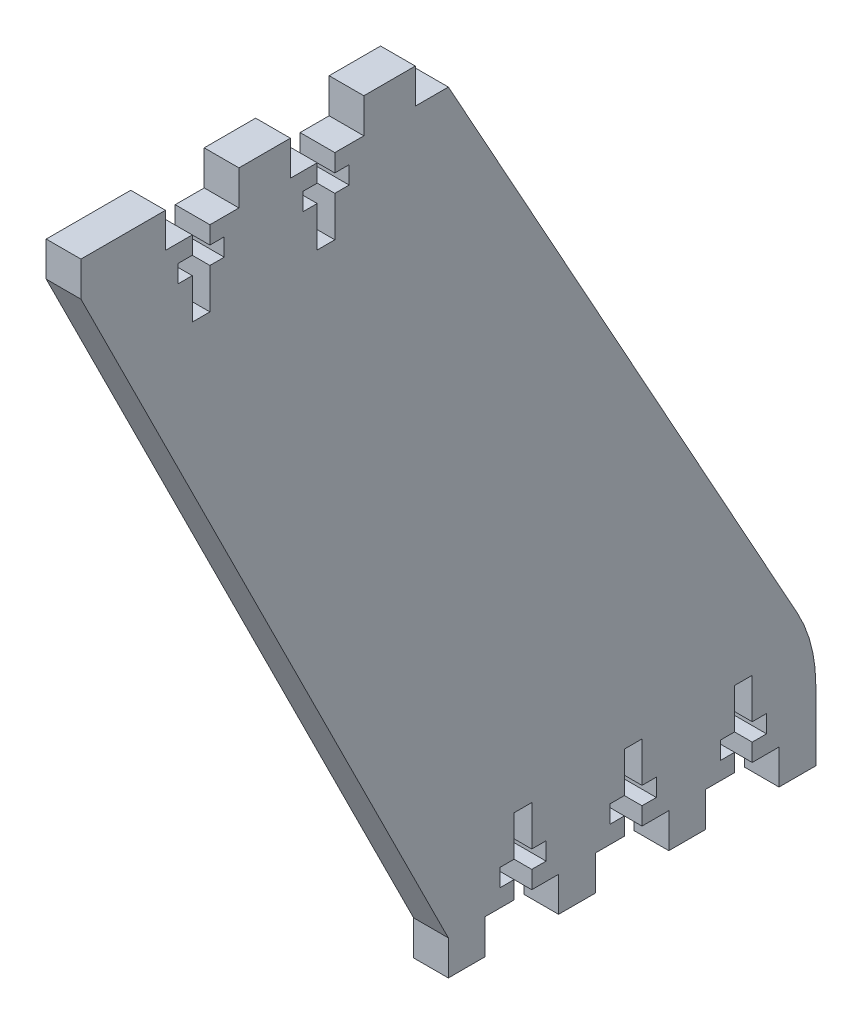
SolidWorks part; units mm, degrees
ref_plane "Front Plane" through (0, 0, 0) normal (0, 0, 1) x (1, 0, 0)
ref_plane "Top Plane" through (0, 0, 0) normal (0, 1, 0) x (1, 0, 0)
ref_plane "Right Plane" through (0, 0, 0) normal (1, 0, 0) x (0, 0, -1)
sketch "Sketch1" plane through (0, 0, 0) normal (1, 0, 0) x (0, 0, -1)
  line L0 (-74.3254, 0) -> (74.3254, 0) construction
  line L1 (-31.75, 0) -> (-95.25, 127.35)
  line L4 (-31.75, 0) -> (0, 17.1799) construction
  line L5 (-95.25, 127.35) -> (-95.25, 133.35)
  line L6 (-95.25, 133.35) -> (-80.645, 133.35)
  line L7 (-80.645, 133.35) -> (-80.645, 127.35)
  line L8 (-80.645, 127.35) -> (-67.945, 127.35)
  line L9 (-67.945, 127.35) -> (-67.945, 133.35)
  line L10 (-67.945, 133.35) -> (-59.055, 133.35)
  line L11 (-59.055, 133.35) -> (-59.055, 127.35)
  line L12 (-59.055, 127.35) -> (-46.355, 127.35)
  line L13 (-46.355, 127.35) -> (-46.355, 133.35)
  line L14 (-46.355, 133.35) -> (-37.465, 133.35)
  line L15 (-37.465, 133.35) -> (-37.465, 127.35)
  line L16 (-37.465, 127.35) -> (-31.75, 127.35)
  line L17 (-31.75, 0) -> (-31.75, -6)
  line L18 (-31.75, -6) -> (-25.4, -6)
  line L19 (-25.4, -6) -> (-25.4, 0)
  line L20 (-25.4, 0) -> (-12.7, 0)
  line L21 (-12.7, 0) -> (-12.7, -6)
  line L22 (-12.7, -6) -> (-6.35, -6)
  line L23 (-6.35, -6) -> (-6.35, 0)
  line L24 (-6.35, 0) -> (6.35, 0)
  line L25 (6.35, 0) -> (6.35, -6)
  line L26 (6.35, -6) -> (12.7, -6)
  line L27 (12.7, -6) -> (12.7, 0)
  line L28 (12.7, 0) -> (25.4, 0)
  line L29 (25.4, 0) -> (25.4, -6)
  line L30 (25.4, -6) -> (31.75, -6)
  line L31 (31.75, -6) -> (31.75, 0)
  line L32 (0, 17.1799) -> (31.75, 0) construction
  line L33 (0, 0) -> (0, 17.1799) construction
  line L34 (-63.5, 133.35) -> (-63.5, 108.2099) construction
  line L35 (31.75, 0) -> (31.75, 6.1358)
  line L36 (28.5696, 18.4423) -> (-31.75, 127.35)
  arc A0 (31.75, 6.1358) -> (28.5696, 18.4423) centre (6.35, 6.1358) ccw
  point P37 (-74.295, 127.35)
  point P38 (-52.705, 127.35)
  point P39 (-19.05, 0)
  point P40 (19.05, 0)
  point P44 (31.75, 12.7)
  line B0 (-18.8595, 13.05) -> (-18.8595, -5.9362) construction
  line B1 (-20.3835, 0) -> (-20.3835, 3.048)
  line B2 (-20.3835, 3.048) -> (-22.86, 3.048)
  line B3 (-22.86, 3.048) -> (-22.86, 6.096)
  line B4 (-22.86, 6.096) -> (-20.3835, 6.096)
  line B5 (-20.3835, 6.096) -> (-20.3835, 13.05)
  line B6 (-20.3835, 13.05) -> (-17.3355, 13.05)
  line B7 (-17.3355, 6.096) -> (-17.3355, 13.05)
  line B8 (-14.859, 6.096) -> (-17.3355, 6.096)
  line B9 (-14.859, 3.048) -> (-14.859, 6.096)
  line B10 (-17.3355, 3.048) -> (-14.859, 3.048)
  line B11 (-17.3355, 0) -> (-17.3355, 3.048)
  line B12 (0.1905, 13.05) -> (0.1905, -5.9362) construction
  line B13 (-1.3335, 0) -> (-1.3335, 3.048)
  line B14 (-1.3335, 3.048) -> (-3.81, 3.048)
  line B15 (-3.81, 3.048) -> (-3.81, 6.096)
  line B16 (-3.81, 6.096) -> (-1.3335, 6.096)
  line B17 (-1.3335, 6.096) -> (-1.3335, 13.05)
  line B18 (-1.3335, 13.05) -> (1.7145, 13.05)
  line B19 (1.7145, 6.096) -> (1.7145, 13.05)
  line B20 (4.191, 6.096) -> (1.7145, 6.096)
  line B21 (4.191, 3.048) -> (4.191, 6.096)
  line B22 (1.7145, 3.048) -> (4.191, 3.048)
  line B23 (1.7145, 0) -> (1.7145, 3.048)
  line B24 (19.2405, 13.05) -> (19.2405, -5.9362) construction
  line B25 (17.7165, 0) -> (17.7165, 3.048)
  line B26 (17.7165, 3.048) -> (15.24, 3.048)
  line B27 (15.24, 3.048) -> (15.24, 6.096)
  line B28 (15.24, 6.096) -> (17.7165, 6.096)
  line B29 (17.7165, 6.096) -> (17.7165, 13.05)
  line B30 (17.7165, 13.05) -> (20.7645, 13.05)
  line B31 (20.7645, 6.096) -> (20.7645, 13.05)
  line B32 (23.241, 6.096) -> (20.7645, 6.096)
  line B33 (23.241, 3.048) -> (23.241, 6.096)
  line B34 (20.7645, 3.048) -> (23.241, 3.048)
  line B35 (20.7645, 0) -> (20.7645, 3.048)
  line B36 (-74.4855, 114.3) -> (-74.4855, 133.2862) construction
  line B37 (-72.9615, 127.35) -> (-72.9615, 124.302)
  line B38 (-72.9615, 124.302) -> (-70.485, 124.302)
  line B39 (-70.485, 124.302) -> (-70.485, 121.254)
  line B40 (-70.485, 121.254) -> (-72.9615, 121.254)
  line B41 (-72.9615, 121.254) -> (-72.9615, 114.3)
  line B42 (-72.9615, 114.3) -> (-76.0095, 114.3)
  line B43 (-76.0095, 121.254) -> (-76.0095, 114.3)
  line B44 (-78.486, 121.254) -> (-76.0095, 121.254)
  line B45 (-78.486, 124.302) -> (-78.486, 121.254)
  line B46 (-76.0095, 124.302) -> (-78.486, 124.302)
  line B47 (-76.0095, 127.35) -> (-76.0095, 124.302)
  line B48 (-52.8955, 114.3) -> (-52.8955, 133.2862) construction
  line B49 (-51.3715, 127.35) -> (-51.3715, 124.302)
  line B50 (-51.3715, 124.302) -> (-48.895, 124.302)
  line B51 (-48.895, 124.302) -> (-48.895, 121.254)
  line B52 (-48.895, 121.254) -> (-51.3715, 121.254)
  line B53 (-51.3715, 121.254) -> (-51.3715, 114.3)
  line B54 (-51.3715, 114.3) -> (-54.4195, 114.3)
  line B55 (-54.4195, 121.254) -> (-54.4195, 114.3)
  line B56 (-56.896, 121.254) -> (-54.4195, 121.254)
  line B57 (-56.896, 124.302) -> (-56.896, 121.254)
  line B58 (-54.4195, 124.302) -> (-56.896, 124.302)
  line B59 (-54.4195, 127.35) -> (-54.4195, 124.302)
  dimension "D12" = 25.4
  dimension "D2" = 63.5
  dimension "D3" = 63.5
  dimension "D4" = 6
  dimension "D5" = 6
  dimension "D6" = 133.35
  dimension "D7" = 12.7
  dimension "D8" = 63.5
  dimension "D9" = 12.7
  dimension "D10" = 6.35
  dimension "D11" = 12.7
  dimension "D13" = 8.89
  dimension "D14" = 5.715
sketch_block_instance "Block-6-32x0_625 T-Nut block-1"
sketch_block "Block-6-32x0_625 T-Nut block" parameters "D1"=3.048, "D2"=13.05, "D3"=8.001, "D4"=3.048, "D5"=3.048
sketch_block_instance "Block-6-32x0_625 T-Nut block-2"
sketch_block_instance "Block-6-32x0_625 T-Nut block-3"
sketch_block_instance "Block-6-32x0_625 T-Nut block-5"
sketch_block_instance "Block-6-32x0_625 T-Nut block-6"
extrude "Boss-Extrude1" add sketch "Sketch1" along normal blind 6
